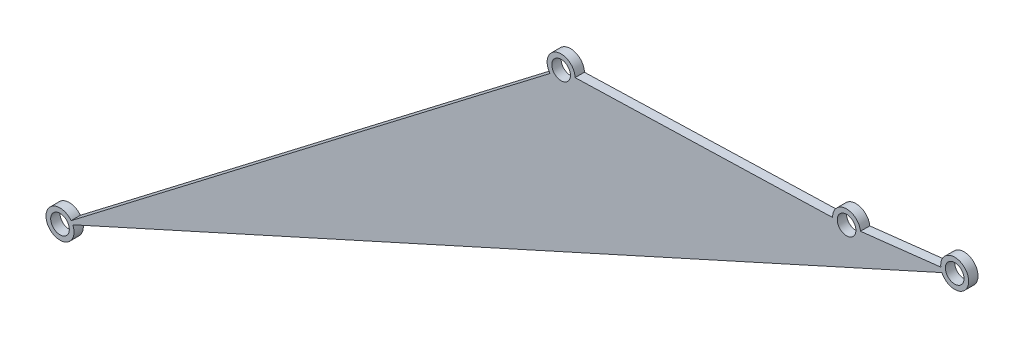
SolidWorks part; units mm, degrees
ref_plane "Plano frontal" through (0, 0, 0) normal (0, 0, 1) x (1, 0, 0)
ref_plane "Plano superior" through (0, 0, 0) normal (0, 1, 0) x (1, 0, 0)
ref_plane "Plano direito" through (0, 0, 0) normal (1, 0, 0) x (0, 0, -1)
sketch "Esboço1" plane through (0, 0, 0) normal (0, 0, 1) x (1, 0, 0)
  line L4 (-43.9661, -24.4107) -> (7.4002, 14.9452)
  line L7 (10.0903, 15.902) -> (37.7081, 16.7216)
  line L8 (40.6979, 16.9353) -> (49.3125, 17.9132)
  line L9 (49.4363, 17.4642) -> (-43.7901, -24.7047)
  circle A0 centre (-45.1568, -25.3229) radius 1
  circle A1 centre (8.5909, 15.8575) radius 1
  circle A2 centre (39.2074, 16.7661) radius 1
  circle A3 centre (50.803, 18.0824) radius 1
  arc A4 (49.4363, 17.4642) -> (49.3125, 17.9132) centre (50.803, 18.0824) ccw
  arc A5 (40.6979, 16.9353) -> (37.7081, 16.7216) centre (39.2074, 16.7661) ccw
  arc A6 (10.0903, 15.902) -> (7.4002, 14.9452) centre (8.5909, 15.8575) ccw
  arc A7 (-43.9661, -24.4107) -> (-43.7901, -24.7047) centre (-45.1568, -25.3229) ccw
  dimension "D6" = 0.5
  dimension "D1" = 67.71
  dimension "D2" = 30.63
  dimension "D3" = 11.67
  dimension "D4" = 105.32
extrude "Ressalto-extrusão1" add sketch "Esboço1" along normal blind 1
